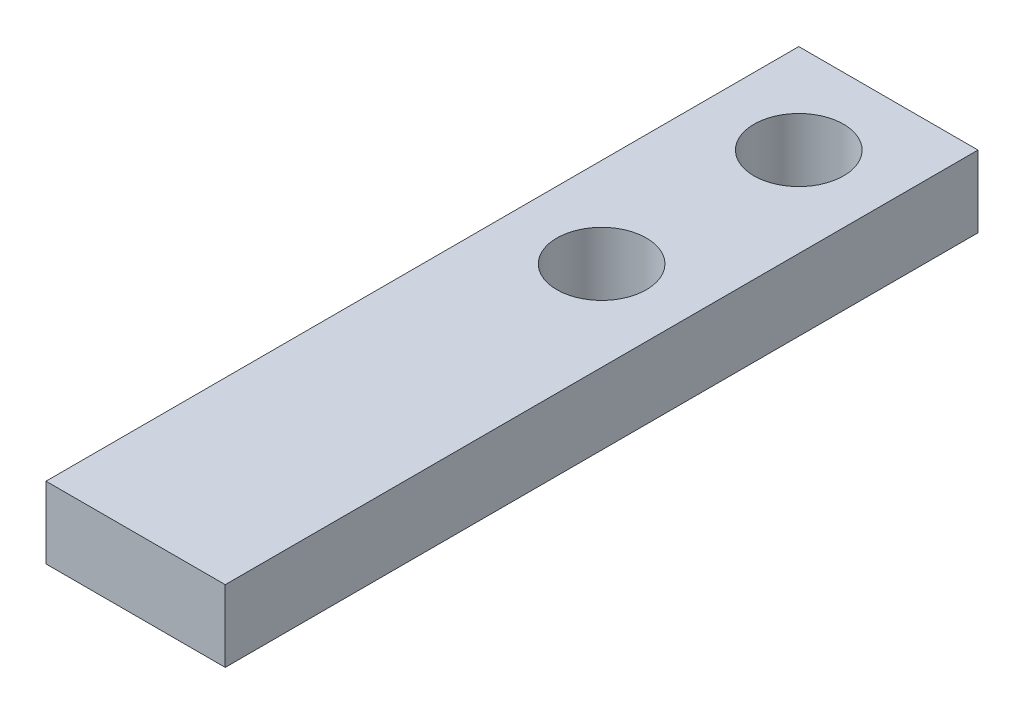
SolidWorks part; units mm, degrees
ref_plane "Front Plane" through (0, 0, 0) normal (0, 0, 1) x (1, 0, 0)
ref_plane "Top Plane" through (0, 0, 0) normal (0, 1, 0) x (1, 0, 0)
ref_plane "Right Plane" through (0, 0, 0) normal (1, 0, 0) x (0, 0, -1)
sketch "Sketch1" plane through (0, 0, 0) normal (0, 1, 0) x (1, 0, 0)
  line L0 (-5, 21) -> (5, 21)
  line L1 (-5, 21) -> (-5, -21)
  line L2 (-5, -21) -> (5, -21)
  line L3 (5, 21) -> (5, -21)
  circle A0 centre (0, 16) radius 2.5
  circle A1 centre (0, 5) radius 2.5
  point P11 (-0.8339, 21)
  point P12 (-1.0511, 21)
  dimension "D3" = 5
  dimension "D4" = 5
  dimension "D1" = 42
  dimension "D2" = 10
  dimension "D5" = 16
  dimension "D6" = 5
  dimension "D7" = 5
  dimension "D8" = 5
  dimension "D9" = 21
  dimension "D10" = 16
extrude "Boss-Extrude1" add sketch "Sketch1" along normal blind 4
